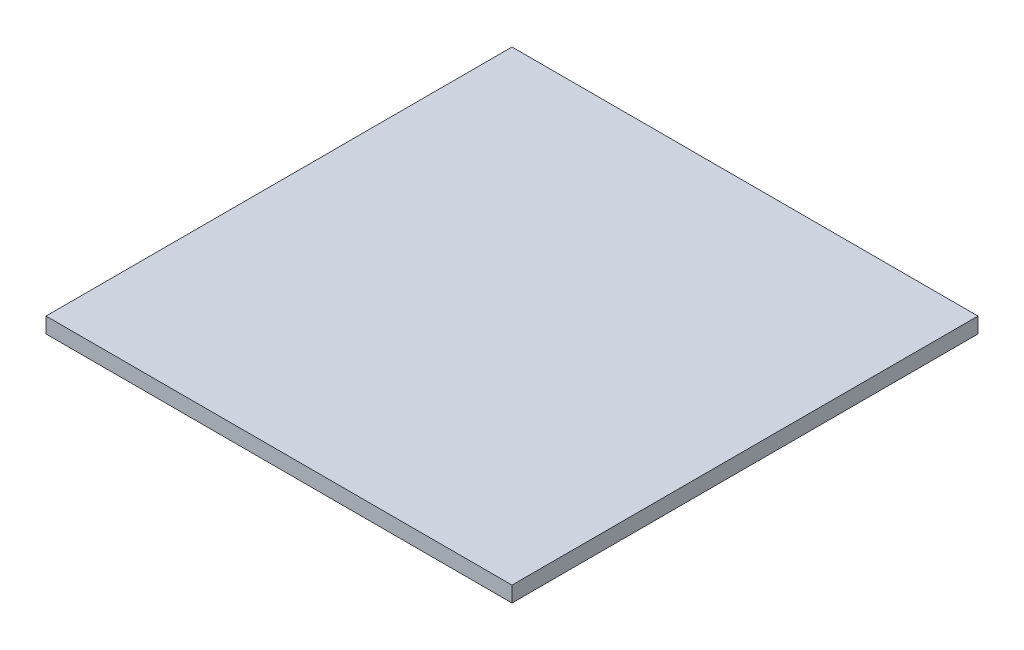
SolidWorks part; units mm, degrees
ref_plane "Front Plane" through (0, 0, 0) normal (0, 0, 1) x (1, 0, 0)
ref_plane "Top Plane" through (0, 0, 0) normal (0, 1, 0) x (1, 0, 0)
ref_plane "Right Plane" through (0, 0, 0) normal (1, 0, 0) x (0, 0, -1)
sketch "Sketch1" plane through (0, 0, 0) normal (0, 1, 0) x (1, 0, 0)
  line L1 (-1500, -1500) -> (1500, -1500)
  line L2 (-1500, -1500) -> (-1500, 1500)
  line L3 (-1500, 1500) -> (1500, 1500)
  line L4 (1500, -1500) -> (1500, 1500)
  line L5 (-1500, -1500) -> (1500, 1500) construction
  line L6 (-1500, 1500) -> (1500, -1500) construction
  point P0 (0, 0)
extrude "Boss-Extrude1" add sketch "Sketch1" along normal blind 100
